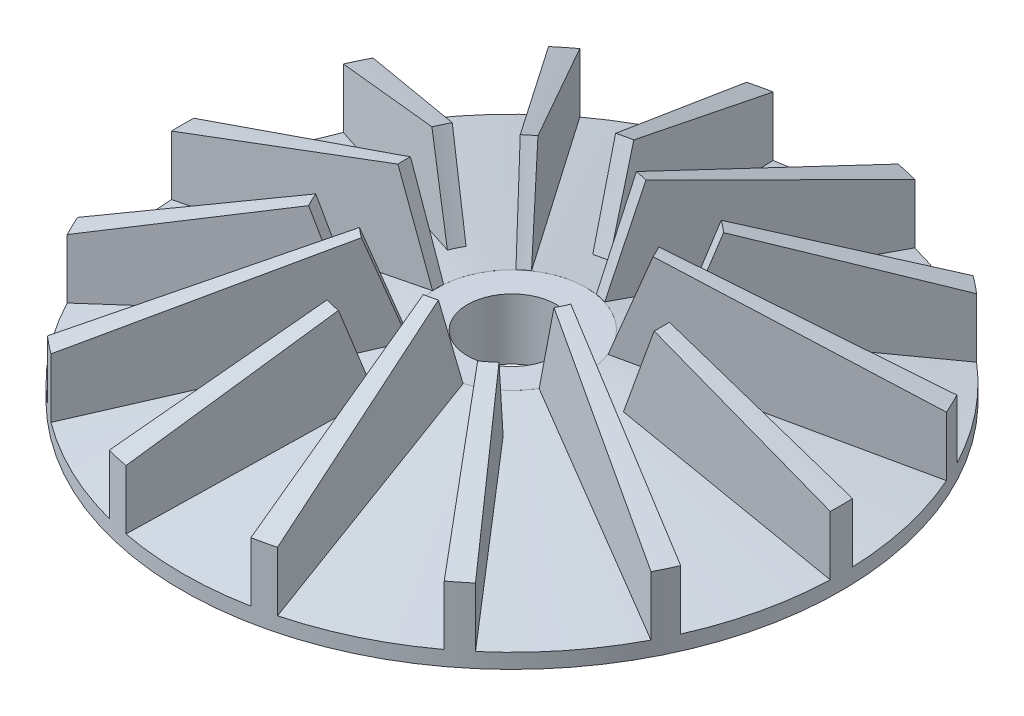
SolidWorks part; units mm, degrees
ref_plane "Front" through (0, 0, 0) normal (0, 0, 1) x (1, 0, 0)
ref_plane "Top" through (0, 0, 0) normal (0, 1, 0) x (1, 0, 0)
ref_plane "Right" through (0, 0, 0) normal (1, 0, 0) x (0, 0, -1)
sketch "Sketch2" plane through (0, 0, 0) normal (0, 0, 1) x (1, 0, 0)
  line L0 (3, 0) -> (22.225, 0)
  line L1 (22.225, 0) -> (22.225, 1)
  line L2 (22.225, 1) -> (3, 4.4601)
  line L3 (0, 0) -> (3, 0) construction
  line L4 (3, 4.4601) -> (3, 0)
  line L5 (0, 0) -> (0, 5) construction
  line L6 (3, 4.4601) -> (0, 5) construction
  dimension "D1" = 3
  dimension "D2" = 22.225
  dimension "D3" = 1
  dimension "D4" = 5
revolve "base" add sketch "Sketch2" angle 360 about L5
sketch "Sketch3" plane through (0, 0, 0) normal (0, -1, 0) x (1, 0, 0)
  line L0 (0, 0) -> (22.225, 0) construction
  line L1 (2.9766, -0.3743) -> (22.2123, -0.75) construction
  line L2 (2.9766, 0.3743) -> (22.2123, 0.75) construction
  line L3 (0, 0) -> (3, 0) construction
  line L4 (2.9766, -0.3743) -> (7.9861, -0.4721) construction
  line L5 (2.9766, 0.3743) -> (7.9861, 0.4721) construction
  line L6 (7.9861, -0.4721) -> (22.2123, -0.75)
  line L7 (22.2123, 0.75) -> (7.9861, 0.4721)
  circle A0 centre (0, 0) radius 22.225 construction
  circle A1 centre (0, 0) radius 3 construction
  arc A2 (2.9766, -0.3743) -> (2.9766, 0.3743) centre (0, 0) ccw construction
  arc A3 (22.2123, -0.75) -> (22.2123, 0.75) centre (0, 0) ccw
  arc A4 (7.9861, -0.4721) -> (7.9861, 0.4721) centre (0, 0) ccw
  dimension "D5" = 16
  dimension "D1" = 0.75
  dimension "D2" = 0.75
  dimension "D3" = 0.375
  dimension "D4" = 0.375
extrude "secondary vanes" add sketch "Sketch3" against normal blind 13
pattern_circular "secondary vane patterm" count 7 over 360 about axis through (0, 0, 0) along (0, 1, 0) of "secondary vanes"
sketch "Sketch6" plane through (0, 0, 0) normal (0, 0, 1) x (1, 0, 0)
  line L0 (8, 3.5602) -> (11.4358, 13)
  line L1 (8, 3.5602) -> (3, 4.4601)
  line L2 (22.2123, 13) -> (7.9861, 13) construction
  line L3 (3, 4.4601) -> (3, 13)
  line L5 (0, 0) -> (0, 18) construction
  line L6 (3, 13) -> (11.4358, 13)
  dimension "D1" = 20
revolve "secondary angle trim" cut sketch "Sketch6" angle 360 about L5
sketch "primary vane ref 1" plane through (0, 0, 0) normal (0, 1, 0) x (1, 0, 0)
  line L0 (0, 0) -> (22.225, 0) construction
  line L1 (0, 0) -> (20.024, -9.6431) construction
  arc A0 (22.2123, -0.75) -> (22.2123, 0.75) centre (0, 0) ccw construction
  arc A1 (14.4355, -16.8987) -> (22.2123, -0.75) centre (0, 0) ccw construction
  dimension "D1" = 25.714
sketch "primary vane ref 2" plane through (0, 0, 0) normal (0, 0, 1) x (1, 0, 0)
  line L0 (0, 0) -> (0, 59.5395) construction
ref_plane "primary vane ref plane" through (0, 0, 0) normal (-0.4339, 0, 0.901) x (0.901, 0, 0.4339)
sketch "Sketch10" plane through (0, 0, 0) normal (0, 1, 0) x (1, 0, 0)
  line L0 (22.225, 0) -> (0, 0) construction
  line L1 (0, 0) -> (20.024, -9.6431) construction
  line L2 (4.6548, -1.8257) -> (20.338, -8.9619)
  line L3 (4.3296, -2.5009) -> (19.6873, -10.3132)
  line L4 (0, 0) -> (4.5048, -2.1694) construction
  arc A0 (22.2123, -0.75) -> (22.2123, 0.75) centre (0, 0) ccw construction
  arc A1 (14.4355, -16.8987) -> (22.2123, -0.75) centre (0, 0) ccw construction
  arc A2 (4.3296, -2.5009) -> (4.6548, -1.8257) centre (0, 0) ccw
  arc A3 (19.6873, -10.3132) -> (20.338, -8.9619) centre (0, 0) ccw
  dimension "D3" = 0.375
  dimension "D4" = 0.375
  dimension "D1" = 25.714
  dimension "D2" = 10
  dimension "D5" = 44.45
  dimension "D6" = 0.75
  dimension "D7" = 0.75
extrude "primary vane extrude" add sketch "Sketch10" along normal blind 13
pattern_circular "primary vane pattern" count 7 over 360 about axis through (0, 0, 0) along (0, 1, 0) of "primary vane extrude"
sketch "Sketch11" plane through (0, 0, 0) normal (-0.4339, 0, 0.901) x (0.901, 0, 0.4339)
  line L0 (5, 4.1001) -> (3, 4.4601)
  line L1 (3, 4.4601) -> (3, 18)
  line L2 (5, 4.1001) -> (10.6385, 19.5916)
  line L5 (0, 0) -> (0, 18) construction
  line L6 (-3, 0) -> (3, 0) construction
  line L7 (10.6385, 19.5916) -> (3, 19.5916)
  line L8 (3, 19.5916) -> (3, 18)
  dimension "D1" = 20
revolve "primary angle trim" cut sketch "Sketch11" angle 360 about L5
sketch "Sketch12" plane through (0, 0, 0) normal (0, 0, 1) x (1, 0, 0)
  line L0 (0, 0) -> (0, 13) construction
  line L1 (0, 0) -> (22.225, 0) construction
  line L2 (22.225, 0) -> (22.225, 5) construction
  line L3 (0, 13) -> (22.225, 5) construction
  line L4 (22.225, 5) -> (22.225, 13)
  line L5 (0, 13) -> (22.225, 13) construction
  line L6 (22.225, 13) -> (7.5827, 17.4078)
  line L7 (7.5827, 17.4078) -> (6.464, 10.6732)
  line L8 (6.464, 10.6732) -> (22.225, 5)
  spline S0 degree 3 poles (7.2193, 13) (6.2563, 10.0333) (5.2933, 7.0665) (4.3296, 4.1001) knots 0 0 0 0 0.009472 0.009472 0.009472 0.009472 construction
  dimension "D1" = 5
  dimension "D2" = 13
revolve "Cut-Revolve5" cut sketch "Sketch12" angle 360 about L0
sketch "Sketch14" plane through (0, 0, 0) normal (-0.4339, 0, 0.901) x (0.901, 0, 0.4339)
  line L0 (4.9859, 4.1001) -> (0, 4.1001)
  line L1 (0, 0) -> (0, 18) construction
  line L2 (0, 4.1001) -> (0, 18)
  line L3 (0, 18) -> (4.9859, 4.1001)
revolve "Cut-Revolve6" cut sketch "Sketch14" angle 360 about L2
equation "\"base outer diameter\"= 1.75in"
equation "\"base outer thickness\" = 1mm"
equation "\"base center thickness\" = 5mm"
equation "\"number of vanes\"= 14"
equation "\"vane outer height`\" = 4mm"
equation "\"vane inner height\" = 8mm"
equation "\"primary vane opening diamater\"= 10mm"
equation "\"bore size\"= 6mm"
equation "\"vane inner thickness\"= .75mm"
equation "\"vane outer thickness\"= 1.5mm"
equation "\"D1@Sketch2\"=\"bore size\"/2"
equation "\"D2@Sketch2\"=\"base outer diameter\"/2"
equation "\"D3@Sketch2\"=\"base outer thickness\""
equation "\"D4@Sketch2\"=\"base center thickness\""
equation "\"D1@Sketch3\"=\"vane outer thickness\"/2"
equation "\"D2@Sketch3\"=\"vane outer thickness\"/2"
equation "\"D3@Sketch3\"=\"vane inner thickness\"/2"
equation "\"D4@Sketch3\"=\"vane inner thickness\"/2"
equation "\"D1@secondary vanes\" = \"vane inner height\" + \"base center thickness\""
equation "\"D5@Sketch3\"=\"secondary vane opening diameter\""
equation "\"primary vane entrance angle\"= 20deg"
equation "\"secondary vane entrance angle\"= 20deg"
equation "\"secondary vane opening diameter\"= 16mm"
equation "\"D1@Sketch6\"=\"secondary vane entrance angle\""
equation "\"D1@primary vane ref 1\" = 360 / \"number of vanes\""
equation "\"D1@Sketch10\"=360/\"number of vanes\""
equation "\"D2@Sketch10\"=\"primary vane opening diamater\""
equation "\"D3@Sketch10\"=\"vane inner thickness\"/2"
equation "\"D4@Sketch10\"=\"vane inner thickness\"/2"
equation "\"D5@Sketch10\"=\"base outer diameter\""
equation "\"D6@Sketch10\"=\"vane outer thickness\"/2"
equation "\"D7@Sketch10\"=\"vane outer thickness\"/2"
equation "\"D1@primary vane extrude\" = \"base center thickness\" + \"vane inner height\""
equation "\"D1@Sketch11\"=\"primary vane entrance angle\""
equation "\"D1@Sketch12\"=\"base outer thickness\"+\"vane outer height`\""
equation "\"D2@Sketch12\"=\"base center thickness\"+ \"vane inner height\""
equation "\"D1@secondary vane patterm\"=\"number of vanes\"/2"
equation "\"D1@primary vane pattern\"=\"number of vanes\"/2"
